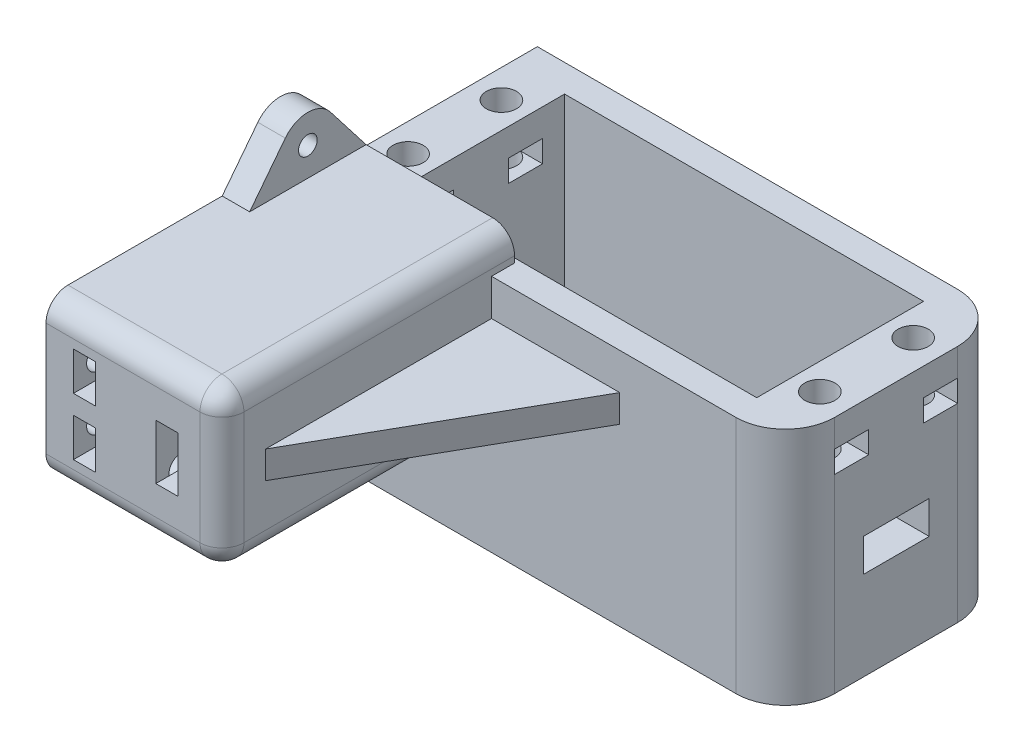
SolidWorks part; units mm, degrees
ref_plane "Front Plane" through (0, 0, 0) normal (0, 0, 1) x (1, 0, 0)
ref_plane "Top Plane" through (0, 0, 0) normal (0, 1, 0) x (1, 0, 0)
ref_plane "Right Plane" through (0, 0, 0) normal (1, 0, 0) x (0, 0, -1)
sketch "Sketch2" plane through (0, 0, 0) normal (0, -1, 0) x (1, 0, 0)
  line L1 (-29.5, -30.2) -> (-32.5, -30.2)
  line L3 (-32.7, -27) -> (-32.7, -30.2)
  line L4 (-32.7, -30.2) -> (-32.5, -30.2)
  line L5 (-32.7, -27) -> (-32.7, 0)
  line L7 (-32.7, 0) -> (-32.7, 0.2)
  line L8 (-32.7, 0.2) -> (32.5, 0.2)
  line L9 (32.5, 0.2) -> (32.7, 0.2)
  line L10 (32.7, 0.2) -> (32.9004, -30.2)
  line L11 (32.9004, -30.2) -> (-29.5, -30.2)
extrude "Boss-Extrude1" add sketch "Sketch2" along normal up to surface (12.5727 mm away) contours L5 L7 L8 L9 L10 L11 L1 L4 L3
sketch "Sketch3" plane through (0, -12.5727, 0) normal (0, -1, 0) x (-1, 0, 0)
  line L1 (-32.7, -5.2) -> (32.6514, -5.2)
  line L2 (32.6514, -5.2) -> (42.6514, -5.2)
  line L3 (42.6514, -5.2) -> (42.6514, 30.2)
  line L4 (42.6514, 30.2) -> (42.6514, 35.2)
  line L5 (42.6514, 35.2) -> (-32.9004, 35.2)
  line L6 (-42.9004, 30.2) -> (-42.9004, -5.2)
  line L7 (-42.9004, 30.2) -> (-42.9004, 35.2)
  line L8 (-42.9004, 35.2) -> (-32.9004, 35.2)
  line L9 (-42.9004, -5.2) -> (-32.7, -5.2)
  line L10 (-32.7, -0.2) -> (32.7, -0.2)
  line L11 (-32.7, -0.2) -> (-32.7, 30.2)
  line L12 (-32.7, 30.2) -> (32.7, 30.2)
  line L13 (32.7, -0.2) -> (32.7, 30.2)
extrude "Boss-Extrude2" add sketch "Sketch3" against normal up to surface (43.5727 mm away) contours L1 L2 L3 L4 L5 L8 L7 L6 L9 | L11 L10 L13 L12
fillet "Fillet1" radius 9 2 edges at (42.9004, 9.2137, -35.2) (42.9004, 9.2137, 5.2)
sketch "Sketch4" plane through (0, 31, 0) normal (0, 1, 0) x (1, 0, 0)
  circle A0 centre (-37.5, 23.5) radius 2.75
  circle A1 centre (-37.5, 6.5) radius 2.75
  circle A2 centre (37.5, 6.5) radius 2.75
  circle A4 centre (37.5, 23.5) radius 2.75
extrude "Cut-Extrude1" cut sketch "Sketch4" against normal blind 20
sketch "Sketch5" plane through (42.9004, 0, 0) normal (1, 0, 0) x (0, 0, -1)
  line L0 (3, 26) -> (6.5, 26)
  line L2 (15, 31) -> (15, 26)
  line L3 (26.2, 31) -> (3.8, 31) construction
  line L4 (23.5, 26) -> (20, 26)
  line L6 (20, 26) -> (20, 22)
  line L7 (20, 22) -> (27, 22)
  line L8 (27, 22) -> (27, 26)
  line L9 (27, 26) -> (23.5, 26)
  line L10 (3, 22) -> (3, 26)
  line L11 (10, 22) -> (3, 22)
  line L12 (10, 26) -> (10, 22)
  line L13 (6.5, 26) -> (10, 26)
  line M8 (26.2, -12.5727) -> (26.2, 31)
  line M10 (3.8, 31) -> (3.8, -12.5727)
extrude "Cut-Extrude2" cut sketch "Sketch5" against normal blind 129 contours L13 L0 L11 L12 M10 | L9 L4 L6 L7 M8
sketch "Sketch6" plane through (0, -12.5727, 0) normal (0, -1, 0) x (1, 0, 0)
  circle A0 centre (19.5, -15) radius 6.7
extrude "Cut-Extrude3" cut sketch "Sketch6" against normal blind 129
sketch "Sketch7" plane through (42.9004, 0, 0) normal (1, 0, 0) x (0, 0, -1)
  line L0 (21.0196, 3.6123) -> (9.0196, 3.6123)
  line L4 (15.0196, 9.6123) -> (9.0196, 9.6123)
  line L5 (9.0196, 9.6123) -> (9.0196, 3.6123)
  line L7 (21.0196, 3.6123) -> (21.0196, 9.6123)
  line L8 (21.0196, 9.6123) -> (15.0196, 9.6123)
extrude "Cut-Extrude6" cut sketch "Sketch7" against normal blind 63
sketch "Sketch8" plane through (0, 0, 5.2) normal (0, 0, 1) x (1, 0, 0)
  line L0 (-42.6514, 31) -> (-42.6514, 32.1123)
  line L1 (-42.6514, 32.1123) -> (-15.9514, 32.1123)
  line L2 (-15.9514, 32.1123) -> (-15.9514, 31)
  line L3 (33.9004, 31) -> (-42.6514, 31) construction
  line L4 (-15.9514, 31) -> (-42.6514, 31)
extrude "Boss-Extrude3" add sketch "Sketch8" against normal offset from surface (4.2 mm away) 1
sketch "Sketch9" plane through (0, 0, 5.2) normal (0, 0, 1) x (1, 0, 0)
  line L0 (-42.6514, 12.1123) -> (-42.6514, 11.7623)
  line L1 (-42.6514, 32.1123) -> (-42.6514, -12.5727) construction
  line L3 (-42.6514, 11.7623) -> (-15.9514, 11.7623)
  line L4 (-15.9514, 11.7623) -> (-15.6014, 11.7623)
  line L5 (-15.6014, 11.7623) -> (-15.6014, 32.1123)
  line L6 (-15.6014, 32.1123) -> (-15.6014, 32.4623)
  line L8 (-15.9514, 31) -> (-15.9514, 32.1123) construction
  line L9 (-15.6014, 32.4623) -> (-42.6514, 32.4623)
  line L10 (-42.6514, 32.4623) -> (-42.6514, 32.1123)
  line L11 (-42.6514, 32.1123) -> (-15.9514, 32.1123)
  line L12 (-15.9514, 32.1123) -> (-15.9514, 12.1123)
  line L13 (-15.9514, 12.1123) -> (-42.6514, 12.1123)
  line L14 (-42.6514, 7.5222) -> (-42.6514, 11.7623)
  line L15 (-10.6014, 32.4623) -> (-10.6014, 11.7623)
  line L16 (-10.6014, 11.7623) -> (-10.6014, 7.5222)
  line L17 (-10.6014, 7.5222) -> (-42.6514, 7.5222)
  line L18 (-42.6514, 7.5222) -> (-42.6514, 11.7623)
  line L19 (-10.6014, 32.4623) -> (-10.6014, 36.1467)
  line L20 (-10.6014, 36.1467) -> (-42.6514, 36.1467)
  line L21 (-42.6514, 36.1467) -> (-42.6514, 32.4623)
  line L22 (-42.6514, 7.5222) -> (-42.6514, 11.7623)
  line M4 (33.9004, 31) -> (-15.9514, 31)
  line M7 (-42.6514, 32.1123) -> (-42.6514, -12.5727)
extrude "Boss-Extrude4" add sketch "Sketch9" along normal offset from surface (41.15 mm away) 0.35 contours L17 L16 L15 L5 L4 L3 M4 M7 | L20 L21 L9 L6 L5 L15 L19 M4
sketch "Sketch10" plane through (0, 0, 5.2) normal (0, 0, -1) x (-1, 0, 0)
  line L0 (10.6014, 31) -> (10.6014, 36.1467)
  line L1 (10.6014, 36.1467) -> (42.6514, 36.1467)
  line L2 (42.6514, 36.1467) -> (42.6514, 31)
  line L3 (42.6514, 31) -> (10.6014, 31)
extrude "Boss-Extrude5" add sketch "Sketch10" along normal up to surface (4.2 mm away) up to face at (-29.3014, 31.5562, 1)
sketch "Sketch12" plane through (-10.6014, 0, 0) normal (1, 0, 0) x (0, 0, -1)
  line L0 (-46.35, 19.3344) -> (-46.35, 24.3344)
  line L1 (-46.35, 24.3344) -> (-46.35, 21.8344)
  line L2 (-5.0253, 19.3344) -> (-5.0253, 24.3344)
  line L3 (-46.35, 21.8344) -> (-46.35, 19.3344)
  line L4 (-46.35, 19.3344) -> (-5.0253, 19.3344)
  line L5 (-46.35, 24.3344) -> (-5.0253, 24.3344)
  line L6 (-46.35, 19.3344) -> (-46.35, 24.3344)
  line M1 (-46.35, 36.1467) -> (-46.35, 7.5222)
  line M3 (-5.2, 7.5222) -> (-5.2, 31)
extrude "Boss-Extrude6" add sketch "Sketch12" along normal blind 23.35 contours L5 L0 L4 M1 M3
sketch "Sketch13" plane through (0, 24.3344, 0) normal (0, 1, 0) x (1, 0, 0)
  line L0 (12.7486, -5.2) -> (-10.6014, -46.35)
  line L1 (-10.6014, -46.35) -> (12.7486, -46.35)
  line L2 (12.7486, -46.35) -> (12.7486, -5.2)
extrude "Cut-Extrude7" cut sketch "Sketch13" against normal blind 23.35
sketch "Sketch14" plane through (-42.6514, 0, 0) normal (-1, 0, 0) x (0, 0, 1)
  line L0 (5.2, -12.5727) -> (27.6007, 7.5222)
  line L1 (27.6007, 7.5222) -> (5.2, 7.5222)
  line L2 (5.2, 7.5222) -> (5.2, -12.5727)
extrude "Boss-Extrude7" add sketch "Sketch14" against normal blind 5
sketch "Sketch15" plane through (0, 0, 46.35) normal (0, 0, 1) x (1, 0, 0)
  line L1 (-10.6014, 36.1467) -> (-42.6514, 36.1467)
  line L2 (-10.6014, 36.1467) -> (-10.6014, 7.5222)
  line L3 (-10.6014, 7.5222) -> (-42.6514, 7.5222)
  line L4 (-42.6514, 36.1467) -> (-42.6514, 7.5222)
extrude "Boss-Extrude8" add sketch "Sketch15" along normal offset from surface (7.95 mm away) 2
fillet "Fillet2" radius 4 1 edges at (-10.6014, 21.8344, 54.3)
fillet "Fillet3" radius 4 6 edges at (-10.6014, 36.1467, 25.65) (-11.773, 36.1467, 53.1284) (-10.6014, 7.5222, 27.75) (-11.773, 7.5222, 53.1284) (-28.6264, 36.1467, 54.3) (-28.6264, 7.5222, 54.3)
sketch "Sketch16" plane through (-42.6514, 0, 0) normal (-1, 0, 0) x (0, 0, 1)
  circle A0 centre (49.7, 27.0623) radius 2.2
  circle A1 centre (49.7, 17.1623) radius 2.2
  circle A2 centre (1.5, 27.0623) radius 2.2
  circle A3 centre (1.5, 17.1623) radius 2.2
extrude "Cut-Extrude8" cut sketch "Sketch16" against normal blind 20
sketch "Sketch17" plane through (0, 0, 54.3) normal (0, 0, 1) x (1, 0, 0)
  line L0 (-42.6514, 21.8344) -> (-37.6514, 21.8344)
  line L2 (-33.6514, 20.1065) -> (-37.6514, 20.1065)
  line L4 (-42.6514, 32.1467) -> (-42.6514, 11.5222) construction
  line L5 (-37.6514, 23.5623) -> (-37.6514, 27.0623)
  line L6 (-37.6514, 27.0623) -> (-37.6514, 30.5623)
  line L7 (-37.6514, 30.5623) -> (-33.6514, 30.5623)
  line L8 (-33.6514, 30.5623) -> (-33.6514, 23.5623)
  line L9 (-33.6514, 23.5623) -> (-37.6514, 23.5623)
  line L10 (-33.6514, 13.1065) -> (-33.6514, 20.1065)
  line L11 (-37.6514, 13.1065) -> (-33.6514, 13.1065)
  line L12 (-37.6514, 16.6065) -> (-37.6514, 13.1065)
  line L13 (-37.6514, 20.1065) -> (-37.6514, 16.6065)
extrude "Cut-Extrude9" cut sketch "Sketch17" against normal blind 41 contours L9 L8 L7 L6 L5 | L2 L13 L12 L11 L10
sketch "Sketch18" plane through (-42.6514, 0, 0) normal (-1, 0, 0) x (0, 0, 1)
  line L0 (54.3, 21.8344) -> (20.0149, 21.8344)
  line L2 (54.3, 32.1467) -> (54.3, 11.5222) construction
  line L3 (1, 36.1467) -> (7.4924, 44.5293)
  line L4 (11.6028, 38.9252) -> (11.6028, 41.1028)
  line L5 (22.2056, 36.1467) -> (15.7132, 44.5293)
  line L6 (1, 36.1467) -> (22.2056, 36.1467)
  circle A0 centre (11.6028, 2.3232) radius 2.4205
  circle A1 centre (11.6028, 41.3457) radius 2.4205
  arc A2 (15.7132, 44.5293) -> (7.4924, 44.5293) centre (11.6028, 41.3457) ccw
  line M14 (50.3, 36.1467) -> (1, 36.1467)
extrude "Boss-Extrude9" add sketch "Sketch18" against normal blind 5 contours L5 A2 L3 A1 M14
sketch "Sketch19" plane through (-42.6514, 0, 0) normal (-1, 0, 0) x (0, 0, 1)
  line L0 (5.2, 22.1123) -> (14.6316, 22.1123)
  line L1 (5.2, 32.4623) -> (5.2, 11.7623) construction
  circle A0 centre (11.6028, 41.3457) radius 2.4205
  circle A1 centre (11.6028, 2.879) radius 2.4205
extrude "Cut-Extrude10" cut sketch "Sketch19" against normal blind 5 contours A1
sketch "Sketch20" plane through (-37.6514, 0, 0) normal (1, 0, 0) x (0, 0, -1)
  circle A0 centre (-11.6028, 2.879) radius 1.7
  circle A1 centre (-11.6028, 41.3457) radius 1.7
  circle A2 centre (-11.6028, 41.3457) radius 2.4205
  circle A3 centre (-11.6028, 2.879) radius 2.4205
extrude "Boss-Extrude10" add sketch "Sketch20" against normal blind 5
sketch "Sketch21" plane through (0, 0, 54.3) normal (0, 0, 1) x (1, 0, 0)
  line L0 (-42.6514, 21.8344) -> (-20.6514, 21.8344)
  line L1 (-42.6514, 32.1467) -> (-42.6514, 11.5222) construction
  line L3 (-18.6514, 26.8344) -> (-22.6514, 26.8344)
  line L4 (-18.6514, 26.8344) -> (-18.6514, 16.8344)
  line L5 (-18.6514, 16.8344) -> (-22.6514, 16.8344)
  line L6 (-22.6514, 26.8344) -> (-22.6514, 16.8344)
  line L7 (-18.6514, 26.8344) -> (-22.6514, 16.8344) construction
  line L8 (-18.6514, 16.8344) -> (-22.6514, 26.8344) construction
extrude "Cut-Extrude11" cut sketch "Sketch21" against normal blind 10 contours L4 L3 L6 L5
